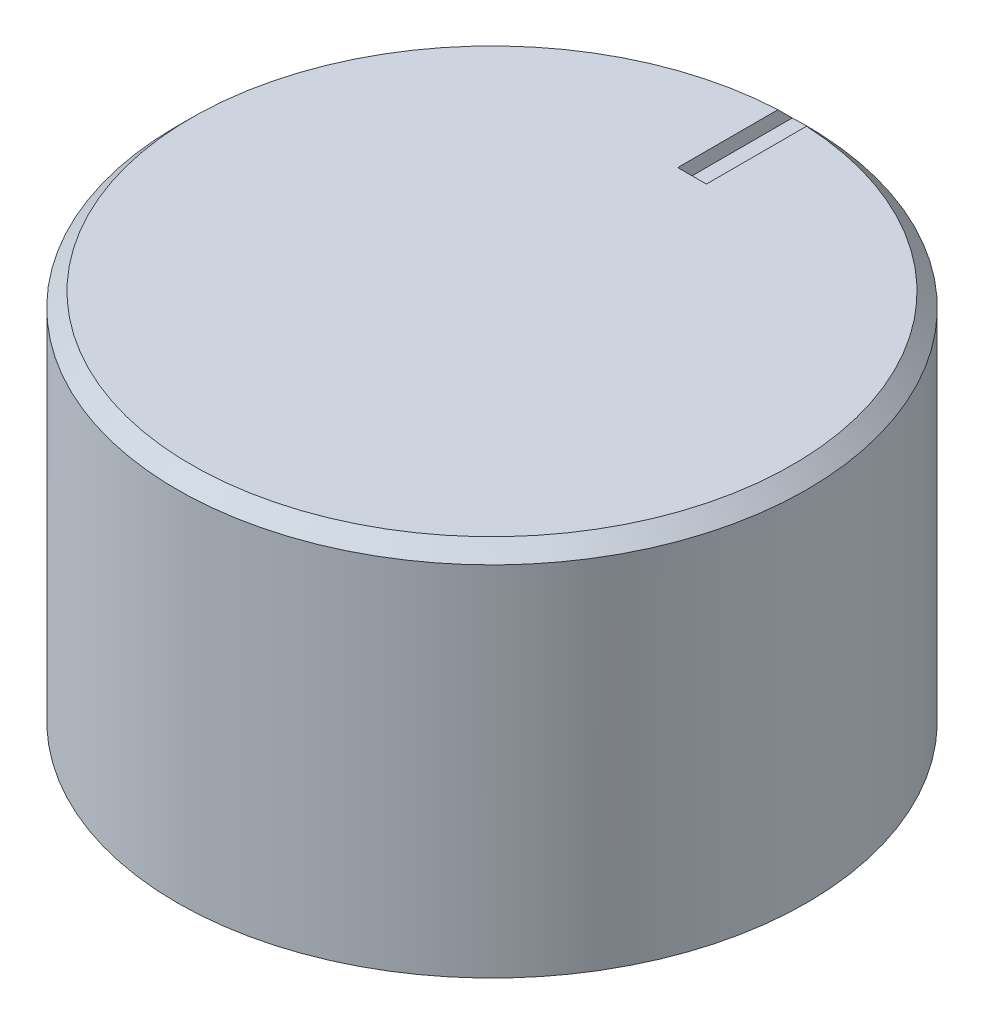
SolidWorks part; units mm, degrees
ref_plane "Front Plane" through (0, 0, 0) normal (0, 0, 1) x (1, 0, 0)
ref_plane "Top Plane" through (0, 0, 0) normal (0, 1, 0) x (1, 0, 0)
ref_plane "Right Plane" through (0, 0, 0) normal (1, 0, 0) x (0, 0, -1)
sketch "Sketch1" plane through (0, 0, 0) normal (0, 1, 0) x (1, 0, 0)
  circle A0 centre (0, 0) radius 11
  circle A1 centre (0, 0) radius 3.175 construction
  dimension "D1" = 22
  dimension "D2" = 6.35
extrude "Boss-Extrude1" add sketch "Sketch1" along normal blind 13
hole_wizard "Hole1" positions "Sketch2" profile "Sketch4" legacy
sketch "Sketch2" plane through (0, 0, 0) normal (0, -1, 0) x (-1, 0, 0)
  point P0 (0, 0)
sketch "Sketch4" plane through (0, 0, 0) normal (1, 0, 0) x (0, 0, -1)
  line L0 (0, 0) -> (0, 10)
  line L1 (0, 10) -> (3.175, 10)
  line L2 (3.175, 10) -> (3.175, 0)
  line L3 (3.175, 0) -> (0, 0)
  line L4 (0, 110) -> (0, -10) construction
  dimension "Diameter" = 6.35
  dimension "Depth" = 10
sketch "Sketch5" plane through (0, 13, 0) normal (0, 1, 0) x (1, 0, 0)
  line L0 (0, 0) -> (0, 11) construction
  line L1 (0.5, 10.9886) -> (0.5, 6.9886)
  line L2 (0.5, 6.9886) -> (-0.5, 6.9886)
  line L3 (-0.5, 6.9886) -> (-0.5, 10.9886)
  circle A0 centre (0, 0) radius 11 construction
  dimension "D1" = 0.5
  dimension "D2" = 1
  dimension "D3" = 4
extrude "Cut-Extrude2" cut sketch "Sketch5" against normal blind 0.5 and the other way through all flip side to cut
chamfer "Chamfer1" distance 0.5 angle 45 1 edges at (0, 13, 11)
